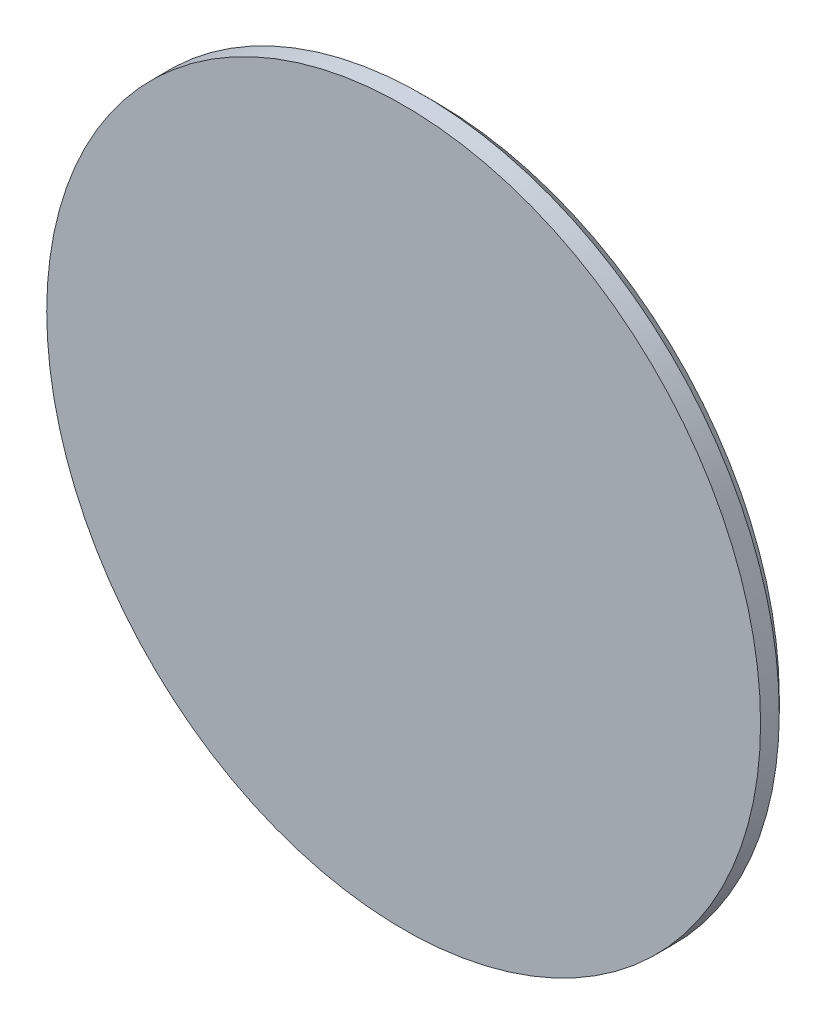
SolidWorks part; units mm, degrees
material "Plywood"
ref_plane "Front Plane" through (0, 0, 0) normal (0, 0, 1) x (1, 0, 0)
ref_plane "Top Plane" through (0, 0, 0) normal (0, 1, 0) x (1, 0, 0)
ref_plane "Right Plane" through (0, 0, 0) normal (1, 0, 0) x (0, 0, -1)
sketch "Sketch1" plane through (0, 0, 0) normal (0, 0, 1) x (1, 0, 0)
  circle A0 centre (-27.4347, 18.3395) radius 33
extrude "Boss-Extrude1" add sketch "Sketch1" along normal blind 3 contours A0
chamfer "Chamfer1" distance 1.27 angle 45 1 edges at (5.5653, 18.3395, 0)
